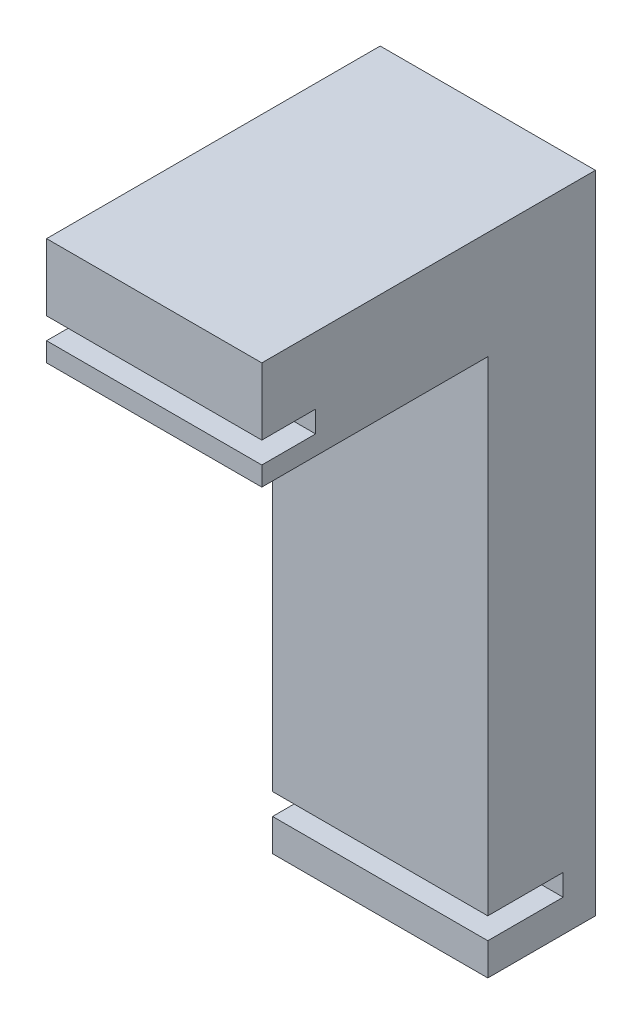
SolidWorks part; units mm, degrees
ref_plane "Alzado" through (0, 0, 0) normal (0, 0, 1) x (1, 0, 0)
ref_plane "Planta" through (0, 0, 0) normal (0, 1, 0) x (1, 0, 0)
ref_plane "Vista lateral" through (0, 0, 0) normal (1, 0, 0) x (0, 0, -1)
sketch "Croquis1" plane through (0, 0, 0) normal (0, 0, 1) x (1, 0, 0)
  line L1 (0, 0) -> (20, 0)
  line L2 (0, 0) -> (0, 60)
  line L3 (0, 60) -> (20, 60)
  line L4 (20, 0) -> (20, 60)
  dimension "D1" = 20
  dimension "D2" = 60
extrude "Saliente-Extruir1" add sketch "Croquis1" along normal blind 31
sketch "Croquis2" plane through (20, 0, 0) normal (1, 0, 0) x (0, 0, -1)
  line L0 (0, 0) -> (0, 60) construction
  line L1 (-31, 0) -> (-10, 0)
  line L2 (-31, 0) -> (-31, 50)
  line L3 (-31, 50) -> (-10, 50)
  line L4 (-10, 0) -> (-10, 50)
  line L5 (-31, 60) -> (0, 60) construction
  dimension "D1" = 10
  dimension "D2" = 10
extrude "Cortar-Extruir1" cut sketch "Croquis2" against normal up to next
sketch "Croquis3" plane through (20, 0, 0) normal (1, 0, 0) x (0, 0, -1)
  line L0 (-31, 50) -> (-31, 60) construction
  line L1 (-31, 53.7836) -> (-26, 53.7836)
  line L2 (-31, 53.7836) -> (-31, 51.7836)
  line L3 (-31, 51.7836) -> (-26, 51.7836)
  line L4 (-26, 53.7836) -> (-26, 51.7836)
  dimension "D1" = 2
  dimension "D2" = 5
extrude "Cortar-Extruir2" cut sketch "Croquis3" against normal up to next
sketch "Croquis4" plane through (20, 0, 0) normal (1, 0, 0) x (0, 0, -1)
  line L0 (-10, 0) -> (-10, 50) construction
  line L1 (-10, 5) -> (-3, 5)
  line L2 (-10, 5) -> (-10, 3)
  line L3 (-10, 3) -> (-3, 3)
  line L4 (-3, 5) -> (-3, 3)
  line L5 (-10, 0) -> (0, 0) construction
  dimension "D1" = 2
  dimension "D2" = 7
  dimension "D3" = 3
extrude "Cortar-Extruir3" cut sketch "Croquis4" against normal up to next
sketch "Croquis5" plane through (20, 0, 0) normal (1, 0, 0) x (0, 0, -1)
  line L0 (-3, 4) -> (-100, 4) construction
  line L1 (-3, 3) -> (-3, 5) construction
  line L2 (-51.5, 4) -> (-51.5, 64.4802) construction
  dimension "D1" = 97
ref_plane "Plano1" through (0, 0, 51.5) normal (0, 0, 1) x (1, 0, 0)
